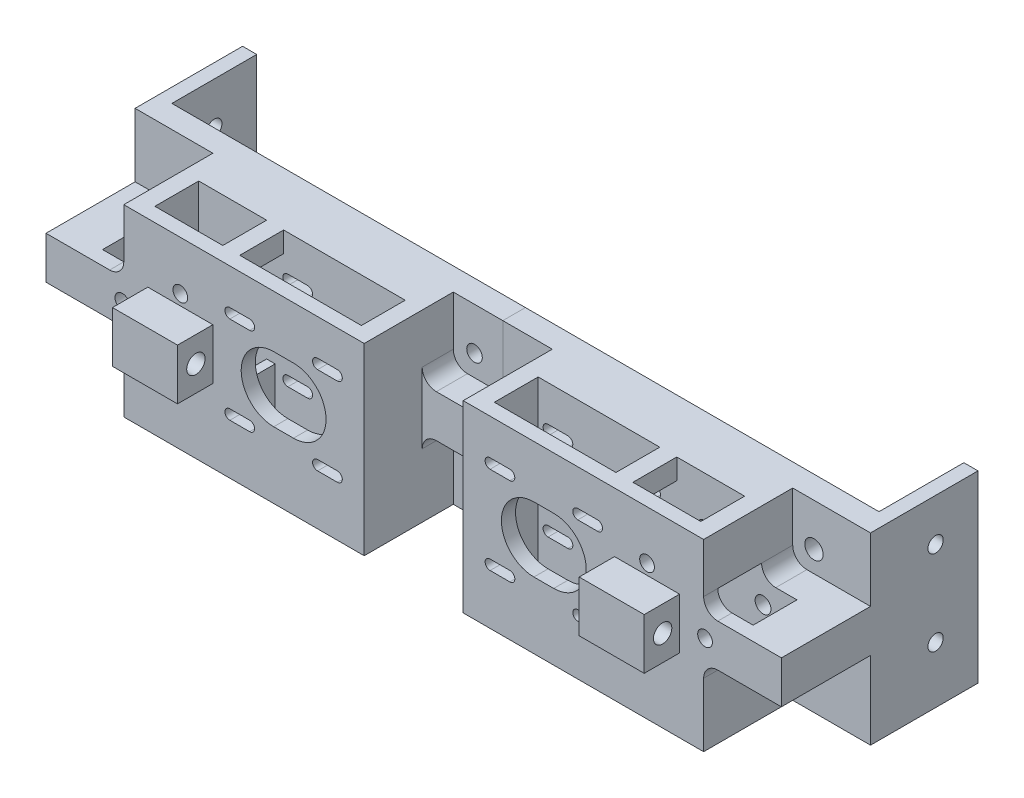
SolidWorks part; units mm, degrees
ref_plane "Front Plane" through (0, 0, 0) normal (0, 0, 1) x (1, 0, 0)
ref_plane "Top Plane" through (0, 0, 0) normal (0, 1, 0) x (1, 0, 0)
ref_plane "Right Plane" through (0, 0, 0) normal (1, 0, 0) x (0, 0, -1)
sketch "Sketch1" plane through (0, 0, 0) normal (0, 0, 1) x (1, 0, 0)
  line L0 (-62.5, 0) -> (-62.5, 30) construction
  line L1 (0, 0) -> (-125, 0)
  line L2 (0, 0) -> (0, 60)
  line L3 (0, 60) -> (-125, 60)
  line L4 (-125, 0) -> (-125, 60)
  line L5 (-15, 15) -> (-115, 15) construction
  line L6 (-15, 15) -> (-15, 45) construction
  line L7 (-15, 45) -> (-115, 45) construction
  line L8 (-115, 15) -> (-115, 45) construction
  line L11 (-62.5, 30) -> (0, 30) construction
  circle A0 centre (-42.5, 42.725) radius 2.8
  circle A1 centre (-22, 30) radius 2.8
  circle A2 centre (-15, 45) radius 3.25
  circle A3 centre (-15, 15) radius 3.25
  circle A4 centre (-115, 15) radius 2.75
  circle A5 centre (-115, 45) radius 2.75
  point P4 (-42.5, 42.725)
  point P8 (-22, 30)
  point P11 (-62.5, 30)
  dimension "D5" = 5.6
  dimension "D8" = 5.6
  dimension "D11" = 6.5
  dimension "D12" = 6.5
  dimension "D13" = 5.5
  dimension "D14" = 5.5
  dimension "D1" = 60
  dimension "D2" = 125
  dimension "D3" = 17.275
  dimension "D4" = 42.5
  dimension "D6" = 30
  dimension "D7" = 22
  dimension "D9" = 10
  dimension "D10" = 15
  dimension "D15" = 15
  dimension "D16" = 15
extrude "Boss-Extrude1" add sketch "Sketch1" along normal blind 19
sketch "Sketch2" plane through (0, 0, 19) normal (0, 0, 1) x (1, 0, 0)
  line L0 (-62.5, 60) -> (-62.5, 0) construction
  line L1 (0, 0) -> (-22.5, 0)
  line L2 (0, 0) -> (0, 22.5)
  line L3 (0, 22.5) -> (-17.5, 22.5)
  line L4 (-22.5, 0) -> (-22.5, 17.5)
  line L5 (0, 60) -> (-22.5, 60)
  line L6 (0, 60) -> (0, 37.5)
  line L7 (0, 37.5) -> (-17.5, 37.5)
  line L8 (-22.5, 60) -> (-22.5, 42.5)
  line L9 (0, 60) -> (-125, 60) construction
  line L10 (-125, 0) -> (0, 0) construction
  line L11 (-107.5, 60) -> (-107.5, 42.5)
  line L12 (-125, 37.5) -> (-112.5, 37.5)
  line L13 (-125, 60) -> (-125, 37.5)
  line L14 (-125, 60) -> (-107.5, 60)
  line L19 (-125, 60) -> (-125, 0) construction
  line L20 (-62.5, 30) -> (-125, 30) construction
  line L21 (-125, 0) -> (-107.5, 0)
  line L22 (-125, 0) -> (-125, 22.5)
  line L23 (-125, 22.5) -> (-112.5, 22.5)
  line L24 (-107.5, 0) -> (-107.5, 17.5)
  arc A0 (-17.5, 22.5) -> (-22.5, 17.5) centre (-17.5, 17.5) ccw
  arc A1 (-17.5, 37.5) -> (-22.5, 42.5) centre (-17.5, 42.5) cw
  arc A2 (-112.5, 37.5) -> (-107.5, 42.5) centre (-112.5, 42.5) ccw
  arc A4 (-112.5, 22.5) -> (-107.5, 17.5) centre (-112.5, 17.5) cw
  dimension "D5" = 5
  dimension "D7" = 5
  dimension "D1" = 22.5
  dimension "D2" = 22.5
  dimension "D3" = 22.5
  dimension "D4" = 22.5
  dimension "D6" = 17.5
extrude "Cut-Extrude1" cut sketch "Sketch2" against normal blind 11
sketch "Sketch3" plane through (0, 0, 0) normal (0, 0, -1) x (-1, 0, 0)
  circle A0 centre (22, 30) radius 3.25
  circle A1 centre (42.5, 42.725) radius 3.25
  dimension "D1" = 6.5
  dimension "D2" = 6.5
extrude "Cut-Extrude2" cut sketch "Sketch3" against normal blind 8
ref_plane "Plane1" through (0, 0, 34.5) normal (0, 0, 1) x (1, 0, 0)
sketch "Sketch4" plane through (0, 0, 34.5) normal (0, 0, 1) x (1, 0, 0)
  line L0 (-107.5, 60) -> (-107.5, 0)
  line L1 (-107.5, 0) -> (-22.5, 0)
  line L2 (-22.5, 17.5) -> (-22.5, 0) construction
  line L3 (-22.5, 0) -> (0, 0) construction
  line L4 (-22.5, 0) -> (-22.5, 17.5)
  line L5 (-22.5, 17.5) -> (-22.5, 0) construction
  line L6 (-107.5, 60) -> (-22.5, 60)
  line L7 (-22.5, 60) -> (-22.5, 42.5)
  line L8 (-17.5, 37.5) -> (0, 37.5)
  line L9 (0, 37.5) -> (0, 22.5)
  line L10 (0, 22.5) -> (-17.5, 22.5)
  arc A0 (-22.5, 17.5) -> (-17.5, 22.5) centre (-17.5, 17.5) cw
  arc A1 (-17.5, 37.5) -> (-22.5, 42.5) centre (-17.5, 42.5) cw
extrude "Boss-Extrude2" add sketch "Sketch4" along normal blind 5 separate body
sketch "Sketch5" plane through (0, 0, 19) normal (0, 0, 1) x (1, 0, 0)
  line L1 (-107.5, 0) -> (-101.5, 0)
  line L2 (-107.5, 0) -> (-107.5, 60)
  line L3 (-107.5, 60) -> (-101.5, 60)
  line L4 (-101.5, 0) -> (-101.5, 60)
  line L5 (-22.5, 0) -> (-28.5, 0)
  line L6 (-22.5, 0) -> (-22.5, 17.5)
  line L7 (-22.5, 17.5) -> (-28.5, 17.5)
  line L8 (-28.5, 0) -> (-28.5, 17.5)
  line L9 (-22.5, 60) -> (-28.5, 60)
  line L10 (-22.5, 60) -> (-22.5, 42.5)
  line L11 (-22.5, 42.5) -> (-28.5, 42.5)
  line L12 (-28.5, 60) -> (-28.5, 42.5)
  line L17 (-107.5, 42.5) -> (-107.5, 60) construction
  line L18 (-22.5, 60) -> (-107.5, 60) construction
  line L19 (-107.5, 0) -> (-22.5, 0) construction
  line L20 (-58.5, 60) -> (-52.5, 60)
  line L21 (-58.5, 60) -> (-58.5, 52.725)
  line L22 (-58.5, 52.725) -> (-52.5, 52.725)
  line L23 (-52.5, 60) -> (-52.5, 52.725)
  line L24 (-52.5, 0) -> (-55.5, 0)
  line L25 (-52.5, 0) -> (-52.5, 17.5)
  line L26 (-52.5, 17.5) -> (-55.5, 17.5)
  line L27 (-55.5, 0) -> (-55.5, 17.5)
  line L28 (-17.5, 37.5) -> (0, 37.5) construction
  line L29 (0, 22.5) -> (-10, 22.5)
  line L30 (0, 22.5) -> (0, 37.5)
  line L31 (0, 37.5) -> (-10, 37.5)
  line L32 (-10, 22.5) -> (-10, 37.5)
  circle A0 centre (-42.5, 42.725) radius 2.8 construction
  dimension "D1" = 6
  dimension "D2" = 10
  dimension "D3" = 6
  dimension "D4" = 17.5
  dimension "D5" = 17.5
  dimension "D6" = 10
  dimension "D7" = 10
  dimension "D8" = 6
  dimension "D9" = 3
extrude "Boss-Extrude3" add sketch "Sketch5" along normal up to next
sketch "Sketch6" plane through (0, 0, 39.5) normal (0, 0, 1) x (1, 0, 0)
  line L0 (-82.5, 30) -> (-75.5, 30) construction
  line L1 (-82.5, 41.5) -> (-75.5, 41.5)
  line L2 (-82.5, 18.5) -> (-75.5, 18.5)
  line L3 (-75.5, 30) -> (0, 30) construction
  line L4 (0, 22.5) -> (0, 37.5) construction
  line L5 (-91, 45.5) -> (-98, 45.5) construction
  line L6 (-91, 43.75) -> (-98, 43.75)
  line L7 (-91, 47.25) -> (-98, 47.25)
  line L8 (-67, 45.5) -> (-60, 45.5) construction
  line L9 (-67, 47.25) -> (-60, 47.25)
  line L10 (-67, 43.75) -> (-60, 43.75)
  line L11 (-91, 14.5) -> (-98, 14.5) construction
  line L12 (-91, 12.75) -> (-98, 12.75)
  line L13 (-91, 16.25) -> (-98, 16.25)
  line L14 (-67, 14.5) -> (-60, 14.5) construction
  line L15 (-67, 16.25) -> (-60, 16.25)
  line L16 (-67, 12.75) -> (-60, 12.75)
  line L17 (-94.5, 14.5) -> (-94.5, 45.5) construction
  line L18 (-63.5, 45.5) -> (-63.5, 14.5) construction
  arc A0 (-82.5, 41.5) -> (-82.5, 18.5) centre (-82.5, 30) ccw
  arc A1 (-75.5, 18.5) -> (-75.5, 41.5) centre (-75.5, 30) ccw
  arc A2 (-91, 43.75) -> (-91, 47.25) centre (-91, 45.5) ccw
  arc A3 (-98, 47.25) -> (-98, 43.75) centre (-98, 45.5) ccw
  arc A4 (-67, 47.25) -> (-67, 43.75) centre (-67, 45.5) ccw
  arc A5 (-60, 43.75) -> (-60, 47.25) centre (-60, 45.5) ccw
  arc A6 (-91, 12.75) -> (-91, 16.25) centre (-91, 14.5) ccw
  arc A7 (-98, 16.25) -> (-98, 12.75) centre (-98, 14.5) ccw
  arc A8 (-67, 16.25) -> (-67, 12.75) centre (-67, 14.5) ccw
  arc A9 (-60, 12.75) -> (-60, 16.25) centre (-60, 14.5) ccw
  point P2 (-79, 30)
  point P12 (-94.5, 45.5)
  point P19 (-63.5, 45.5)
  point P26 (-94.5, 14.5)
  point P33 (-63.5, 14.5)
  dimension "D8" = 1.75
  dimension "D11" = 1.75
  dimension "D12" = 1.75
  dimension "D15" = 1.75
  dimension "D1" = 7
  dimension "D2" = 23
  dimension "D3" = 75.5
  dimension "D4" = 15.5
  dimension "D5" = 15.5
  dimension "D6" = 15.5
  dimension "D7" = 15.5
  dimension "D9" = 7
  dimension "D10" = 7
  dimension "D13" = 7
  dimension "D14" = 7
extrude "Cut-Extrude3" cut sketch "Sketch6" against normal through all
sketch "Sketch7" plane through (0, 0, 39.5) normal (0, 0, 1) x (1, 0, 0)
  line L1 (-54, 39) -> (-31, 39)
  line L2 (-54, 39) -> (-54, 21)
  line L3 (-54, 21) -> (-31, 21)
  line L4 (-31, 39) -> (-31, 21)
  arc A0 (-82.5, 41.5) -> (-82.5, 18.5) centre (-82.5, 30) ccw construction
  dimension "D1" = 21.5
  dimension "D2" = 18
  dimension "D3" = 9
  dimension "D4" = 23
extrude "Boss-Extrude4" add sketch "Sketch7" along normal blind 12.5
sketch "Sketch8" plane through (-31, 0, 0) normal (1, 0, 0) x (0, 0, -1)
  line L0 (-39.5, 21) -> (-39.5, 39) construction
  line L1 (-52, 39) -> (-39.5, 39) construction
  circle A0 centre (-45.5, 30) radius 3.25
  dimension "D1" = 6.5
  dimension "D2" = 6
  dimension "D3" = 9
extrude "Cut-Extrude4" cut sketch "Sketch8" against normal through all
sketch "Sketch9" plane through (0, 0, 0) normal (0, -1, 0) x (1, 0, 0)
  line L0 (-125, 8) -> (-107.5, 8)
  line L1 (-107.5, 8) -> (-107.5, 39.5)
  line L2 (-107.5, 8) -> (-107.5, 39.5) construction
  line L3 (-107.5, 39.5) -> (-22.5, 39.5)
  line L4 (-22.5, 39.5) -> (-22.5, 8)
  line L5 (-22.5, 8) -> (0, 8)
  line L6 (0, 8) -> (0, -30)
  line L7 (0, -30) -> (-125, -30)
  line L8 (-125, -30) -> (-125, 8)
  line L9 (-125, 0) -> (0, 0) construction
  line L10 (-52.5, 34.5) -> (-28.5, 34.5)
  line L11 (-52.5, 34.5) -> (-52.5, 19)
  line L12 (-52.5, 19) -> (-28.5, 19)
  line L13 (-28.5, 34.5) -> (-28.5, 19)
  line L14 (-55.5, 34.5) -> (-101.5, 34.5)
  line L15 (-55.5, 34.5) -> (-55.5, 19)
  line L16 (-55.5, 19) -> (-101.5, 19)
  line L17 (-101.5, 34.5) -> (-101.5, 19)
  line L18 (-125, -15) -> (0, -15) construction
  circle A0 centre (-110, -15) radius 2.7
  circle A1 centre (-80, -15) radius 2.7
  circle A2 centre (-45, -15) radius 2.7
  circle A3 centre (-15, -15) radius 2.7
  dimension "D3" = 15
  dimension "D4" = 30
  dimension "D5" = 15
  dimension "D6" = 30
  dimension "D7" = 5.4
  dimension "D8" = 5.4
  dimension "D9" = 5.4
  dimension "D10" = 5.4
  dimension "D1" = 30
  dimension "D2" = 15
extrude "Boss-Extrude5" add sketch "Sketch9" along normal blind 5
sketch "Sketch10" plane through (0, 0, 0) normal (1, 0, 0) x (0, 0, -1)
  line L0 (-39.5, 37.5) -> (-39.5, 22.5)
  line L1 (-39.5, 22.5) -> (-8, 22.5)
  line L2 (-8, 22.5) -> (-8, -5)
  line L3 (-8, -5) -> (30, -5)
  line L4 (30, -5) -> (30, 60)
  line L5 (-39.5, 37.5) -> (-8, 37.5)
  line L6 (-8, 37.5) -> (-8, 60)
  line L7 (-8, 60) -> (30, 60)
  line L8 (15, 0) -> (15, 60) construction
  line L9 (30, 0) -> (0, 0) construction
  circle A0 centre (15, 45) radius 2.7
  circle A1 centre (15, 15) radius 2.7
  dimension "D1" = 15
  dimension "D2" = 30
  dimension "D3" = 5.4
  dimension "D4" = 5.4
extrude "Boss-Extrude6" add sketch "Sketch10" along normal blind 5
sketch "Sketch11" plane through (0, 0, 34.5) normal (0, 0, -1) x (-1, 0, 0)
  circle A0 centre (42.5, 42.725) radius 2.6
  circle A1 centre (22, 30) radius 2.6
  dimension "D1" = 5.2
  dimension "D2" = 5.2
extrude "Cut-Extrude5" cut sketch "Sketch11" against normal through all
mirror "Mirror1" about plane through (-125, 0, 19) normal (1, 0, 0) of bodies 111
